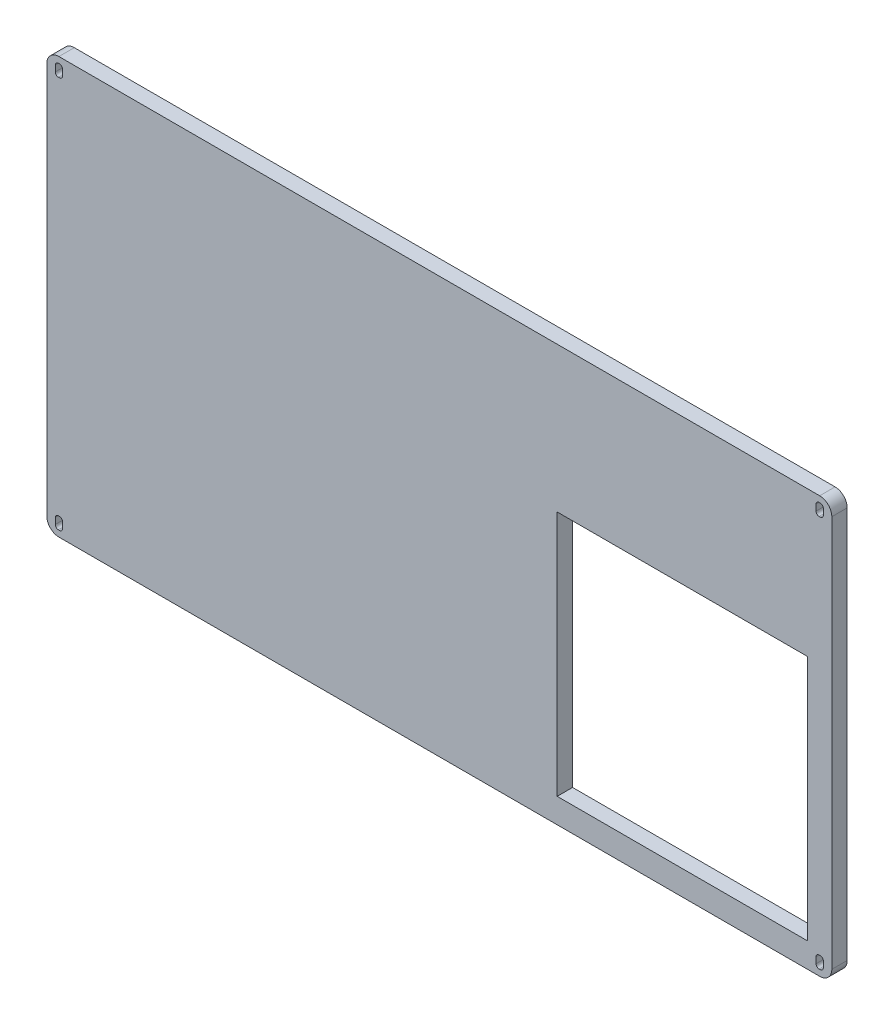
SolidWorks part; units mm, degrees
ref_plane "Front Plane" through (0, 0, 0) normal (0, 0, 1) x (1, 0, 0)
ref_plane "Top Plane" through (0, 0, 0) normal (0, 1, 0) x (1, 0, 0)
ref_plane "Right Plane" through (0, 0, 0) normal (1, 0, 0) x (0, 0, -1)
sketch "Sketch1" plane through (0, 0, 0) normal (0, 0, 1) x (1, 0, 0)
  line L0 (247.3719, -116.8652) -> (246.3719, -116.8652)
  line L1 (-390.8281, 221.5428) -> (256.8719, 221.5428)
  line L2 (-390.8281, 221.5428) -> (-390.8281, -121.8652)
  line L3 (-390.8281, -121.8652) -> (256.8719, -121.8652)
  line L4 (256.8719, 221.5428) -> (256.8719, -121.8652)
  line L5 (249.8719, -114.3652) -> (249.8719, -109.3652)
  line L6 (247.3719, -106.8652) -> (246.3719, -106.8652)
  line L7 (30.2848, -101.5271) -> (236.8719, -101.5271)
  line L8 (30.2848, -101.5271) -> (30.2848, 101.6729)
  line L9 (30.2848, 101.6729) -> (236.8719, 101.6729)
  line L10 (236.8719, -101.5271) -> (236.8719, 101.6729)
  line L11 (243.8719, -114.3652) -> (243.8719, -109.3652)
  line L12 (246.8719, -106.8652) -> (246.8719, -116.8652) construction
  line L13 (249.8719, -111.8652) -> (243.8719, -111.8652) construction
  line L14 (-380.3281, -116.8652) -> (-381.3281, -116.8652)
  line L15 (-383.8281, -114.3652) -> (-383.8281, -109.3652)
  line L16 (-380.3281, -106.8652) -> (-381.3281, -106.8652)
  line L17 (-377.8281, -114.3652) -> (-377.8281, -109.3652)
  line L18 (-380.3281, 206.5448) -> (-381.3281, 206.5448)
  line L19 (-383.8281, 209.0448) -> (-383.8281, 214.0448)
  line L20 (-380.3281, 216.5448) -> (-381.3281, 216.5448)
  line L21 (-377.8281, 209.0448) -> (-377.8281, 214.0448)
  line L22 (247.3719, 206.5448) -> (246.3719, 206.5448)
  line L23 (243.8719, 209.0448) -> (243.8719, 214.0448)
  line L24 (247.3719, 216.5448) -> (246.3719, 216.5448)
  line L25 (249.8719, 209.0448) -> (249.8719, 214.0448)
  arc A0 (247.3719, -116.8652) -> (249.8719, -114.3652) centre (247.3719, -114.3652) ccw
  arc A1 (249.8719, -109.3652) -> (247.3719, -106.8652) centre (247.3719, -109.3652) ccw
  arc A2 (246.3719, -116.8652) -> (243.8719, -114.3652) centre (246.3719, -114.3652) cw
  arc A3 (246.3719, -106.8652) -> (243.8719, -109.3652) centre (246.3719, -109.3652) ccw
  arc A4 (-381.3281, -116.8652) -> (-383.8281, -114.3652) centre (-381.3281, -114.3652) cw
  arc A5 (-381.3281, -106.8652) -> (-383.8281, -109.3652) centre (-381.3281, -109.3652) ccw
  arc A6 (-377.8281, -109.3652) -> (-380.3281, -106.8652) centre (-380.3281, -109.3652) ccw
  arc A7 (-380.3281, -116.8652) -> (-377.8281, -114.3652) centre (-380.3281, -114.3652) ccw
  arc A8 (-381.3281, 206.5448) -> (-383.8281, 209.0448) centre (-381.3281, 209.0448) cw
  arc A9 (-381.3281, 216.5448) -> (-383.8281, 214.0448) centre (-381.3281, 214.0448) ccw
  arc A10 (-377.8281, 214.0448) -> (-380.3281, 216.5448) centre (-380.3281, 214.0448) ccw
  arc A11 (-380.3281, 206.5448) -> (-377.8281, 209.0448) centre (-380.3281, 209.0448) ccw
  arc A12 (246.3719, 206.5448) -> (243.8719, 209.0448) centre (246.3719, 209.0448) cw
  arc A13 (246.3719, 216.5448) -> (243.8719, 214.0448) centre (246.3719, 214.0448) ccw
  arc A14 (249.8719, 214.0448) -> (247.3719, 216.5448) centre (247.3719, 214.0448) ccw
  arc A15 (247.3719, 206.5448) -> (249.8719, 209.0448) centre (247.3719, 209.0448) ccw
  point P26 (246.8719, -111.8652)
  dimension "D9" = 2.5
  dimension "D1" = 647.7
  dimension "D2" = 343.408
  dimension "D3" = 221.5428
  dimension "D4" = 256.8719
  dimension "D5" = 30.2848
  dimension "D6" = 20
  dimension "D7" = 119.87
  dimension "D8" = 20.338
  dimension "D10" = 6
  dimension "D11" = 10
  dimension "D12" = 10
  dimension "D13" = 10
  dimension "D16" = 7
  dimension "D17" = 4.998
  dimension "D18" = 7
  dimension "D14" = 2
  dimension "D15" = 2
extrude "Boss-Extrude1" add sketch "Sketch1" along normal blind 12.7
fillet "Fillet1" radius 10 4 edges at (-390.8281, -121.8652, 6.35) (256.8719, -121.8652, 6.35) (256.8719, 221.5428, 6.35) (-390.8281, 221.5428, 6.35)
